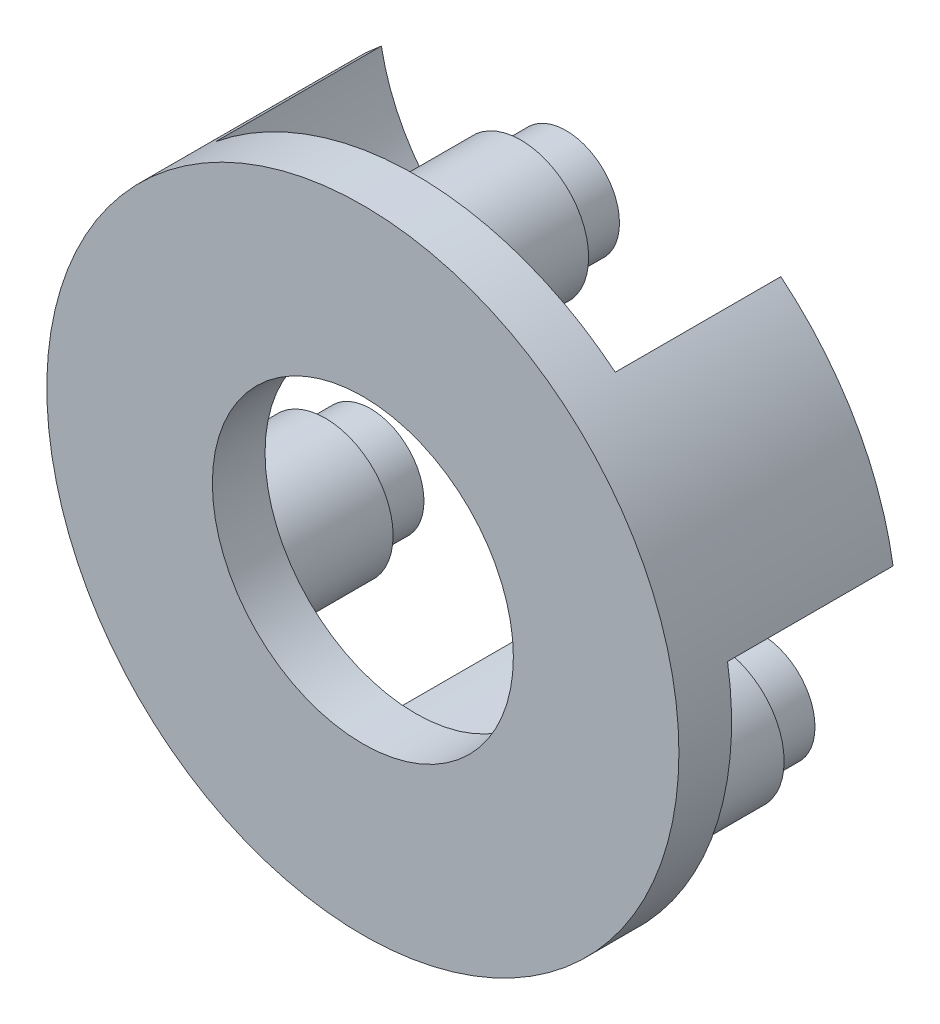
SolidWorks part; units mm, degrees
ref_plane "Front Plane" through (0, 0, 0) normal (0, 0, 1) x (1, 0, 0)
ref_plane "Top Plane" through (0, 0, 0) normal (0, 1, 0) x (1, 0, 0)
ref_plane "Right Plane" through (0, 0, 0) normal (1, 0, 0) x (0, 0, -1)
sketch "Sketch1" plane through (0, 0, 0) normal (0, 0, 1) x (1, 0, 0)
  circle A0 centre (0, 0) radius 21
  dimension "D1" = 42
extrude "Boss-Extrude1" add sketch "Sketch1" along normal blind 3.5 contours A0
sketch "Sketch3" plane through (0, 0, 0) normal (0, 0, -1) x (-1, 0, 0)
  line L0 (0, 7.5) -> (0, 18.75) construction
  arc A4 (-7.459, -19.6307) -> (-3.0219, -12.1292) centre (-16.238, -9.375) ccw
  arc A5 (-13.2712, 16.275) -> (-8.9933, 8.6817) centre (0, 18.75) ccw
  arc A6 (20.7302, 3.3557) -> (12.0152, 3.4476) centre (16.238, -9.375) ccw
  circle A7 centre (0, 0) radius 12.5
  arc A9 (8.9933, 8.6817) -> (13.2712, 16.275) centre (0, 18.75) ccw
  arc A10 (-12.0152, 3.4476) -> (-20.7302, 3.3557) centre (-16.238, -9.375) ccw
  arc A11 (-13.2712, 16.275) -> (-20.7302, 3.3557) centre (0, 0) ccw
  arc A12 (-7.459, -19.6307) -> (7.459, -19.6307) centre (0, 0) ccw
  arc A13 (20.7302, 3.3557) -> (13.2712, 16.275) centre (0, 0) ccw
  arc A14 (3.0219, -12.1292) -> (7.459, -19.6307) centre (16.238, -9.375) ccw
  point P13 (0, 0)
  point P19 (0, 0)
  dimension "D1" = 42
  dimension "D2" = 11.25
  dimension "D5" = 27
  dimension "D7" = 25
  dimension "D6" = 3
sketch "Sketch4" plane through (0, 0, 0) normal (0, 0, -1) x (-1, 0, 0)
  circle A0 centre (0, 0) radius 10
  dimension "D1" = 20
extrude "Cut-Extrude1" cut sketch "Sketch4" against normal blind 8.2
sketch "Sketch11" plane through (0, 0, 0) normal (0, 0, -1) x (-1, 0, 0)
  line L0 (0, 0) -> (0, 15) construction
  line L1 (0, 7.5) -> (0, 18.75) construction
  circle A0 centre (0, 15) radius 1.5
  circle A1 centre (12.9904, -7.5) radius 1.5
  circle A2 centre (-12.9904, -7.5) radius 1.5
  point P12 (0, 0)
  dimension "D2" = 3
  dimension "D3" = 3
  dimension "D1" = 15
extrude "Cut-Extrude2" cut sketch "Sketch11" against normal blind 10
extrude "Boss-Extrude2" add sketch "Sketch3" along normal blind 11 contours A10 A7 A5 L0 | A9 A7 A6 L0 | A14 A7 A4 L0
sketch "Sketch14" plane through (0, 0, -11) normal (0, 0, -1) x (-1, 0, 0)
  line L0 (18.1865, 10.5) -> (0, 0) construction
  line L1 (0, 0) -> (13.8564, 8) construction
  arc A0 (20.7302, 3.3557) -> (13.2712, 16.275) centre (0, 0) ccw construction
  circle A1 centre (13.8564, 8) radius 1.5
  circle A2 centre (0, -16) radius 1.5
  circle A3 centre (-13.8564, 8) radius 1.5
  point P14 (0, 0)
  dimension "D2" = 3
  dimension "D1" = 16
  dimension "D3" = 3
extrude "Cut-Extrude3" cut sketch "Sketch14" against normal blind 5
sketch "Sketch16" plane through (0, 0, 3.5) normal (0, 0, 1) x (1, 0, 0)
  circle A0 centre (0, 15) radius 3.55
  circle A1 centre (12.9904, -7.5) radius 3.55
  circle A2 centre (-12.9904, -7.5) radius 3.55
  point P9 (0, 0)
  dimension "D1" = 7.1
  dimension "D2" = 3
extrude "Boss-Extrude3" add sketch "Sketch16" against normal blind 13.5
sketch "Sketch17" plane through (0, 0, 0) normal (0, 0, -1) x (-1, 0, 0)
  circle A0 centre (0, 15) radius 4.5
  circle A1 centre (12.9904, -7.5) radius 4.5
  circle A2 centre (-12.9904, -7.5) radius 4.5
  point P9 (0, 0)
  dimension "D1" = 9
  dimension "D2" = 3
extrude "Boss-Extrude4" add sketch "Sketch17" along normal blind 7
